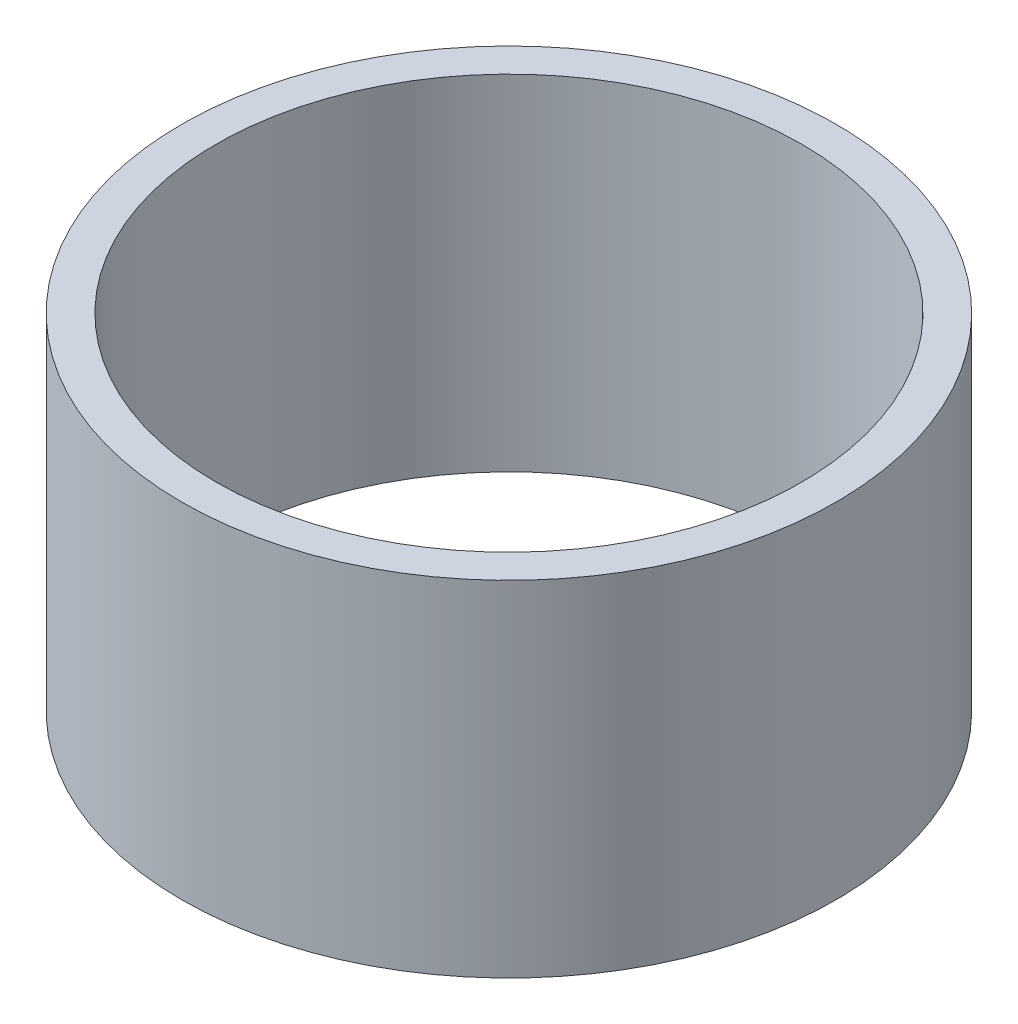
SolidWorks part; units mm, degrees
material "6061 Alloy"
ref_plane "Front Plane" through (0, 0, 0) normal (0, 0, 1) x (1, 0, 0)
ref_plane "Top Plane" through (0, 0, 0) normal (0, 1, 0) x (1, 0, 0)
ref_plane "Right Plane" through (0, 0, 0) normal (1, 0, 0) x (0, 0, -1)
sketch "Sketch1" plane through (0, 0, 0) normal (0, 1, 0) x (1, 0, 0)
  circle A0 centre (0, 0) radius 48.26
  dimension "D1" = 96.52
extrude "Boss-Extrude1" add sketch "Sketch1" along normal blind 50.8
sketch "Sketch2" plane through (0, 50.8, 0) normal (0, 1, 0) x (1, 0, 0)
  circle A0 centre (0, 0) radius 43.18
  dimension "D1" = 86.36
extrude "Cut-Extrude1" cut sketch "Sketch2" against normal blind 50.8
